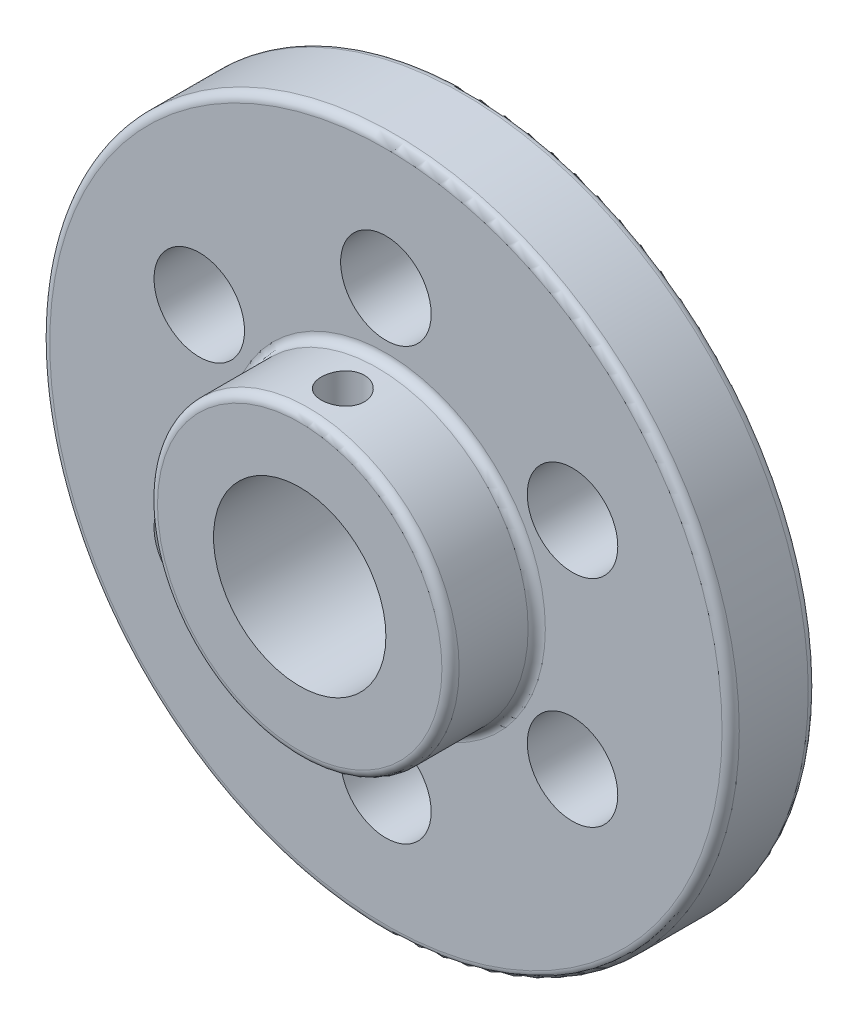
SolidWorks part; units mm, degrees
material "Gray Cast Iron"
ref_plane "Front Plane" through (0, 0, 0) normal (0, 0, 1) x (1, 0, 0)
ref_plane "Top Plane" through (0, 0, 0) normal (0, 1, 0) x (1, 0, 0)
ref_plane "Right Plane" through (0, 0, 0) normal (1, 0, 0) x (0, 0, -1)
sketch "Sketch1" plane through (0, 0, 0) normal (0, 0, 1) x (1, 0, 0)
  circle A0 centre (0, 0) radius 40
  circle A1 centre (0, 0) radius 10
  dimension "D1" = 80
  dimension "D2" = 20
extrude "Boss-Extrude1" add sketch "Sketch1" along normal blind 10
sketch "Sketch2" plane through (0, 0, 10) normal (0, 0, 1) x (1, 0, 0)
  circle A0 centre (0, 0) radius 25 construction
  circle A1 centre (0, 25) radius 5 construction
  dimension "D1" = 50
  dimension "D2" = 10
hole_wizard "M12x1.5 Tapped Hole1" positions "Sketch3" profile "Sketch4" tap size "M12x1.5" standard "ANSI Metric" end condition through all
sketch "Sketch3" plane through (0, 0, 10) normal (0, 0, 1) x (1, 0, 0)
  point P0 (0, 25)
sketch "Sketch4" plane through (0, 25, 10) normal (1, 0, 0) x (0, -1, 0)
  line L0 (0, 0) -> (0, 10)
  line L1 (0, 10) -> (5.25, 10)
  line L2 (5.25, 10) -> (5.25, 0)
  line L5 (5.25, 0) -> (0, 0)
  line L11 (0, -6.35) -> (0, 107.95) construction
  dimension "Thru Tap Drill Dia." = 10.5
  dimension "Thru Tap Drill Depth" = 10
cosmetic thread "Hole Thread1" parameters "D2"=12
pattern_circular "CirPattern1" count 6 over 360 about axis through (0, 0, 0) along (0, 0, 1) of "M12x1.5 Tapped Hole1"
cosmetic thread "Hole Thread2" parameters "D2"=12
cosmetic thread "Hole Thread3" parameters "D2"=12
cosmetic thread "Hole Thread4" parameters "D2"=12
cosmetic thread "Hole Thread5" parameters "D2"=12
cosmetic thread "Hole Thread6" parameters "D2"=12
sketch "Sketch5" plane through (0, 0, 10) normal (0, 0, 1) x (1, 0, 0)
  circle A0 centre (0, 0) radius 17.5
  circle A1 centre (0, 0) radius 10 construction
  circle A2 centre (0, 0) radius 10
  dimension "D1" = 35
extrude "Boss-Extrude2" add sketch "Sketch5" along normal blind 10
ref_plane "Plane1" through (0, 17.5, 0) normal (0, 1, 0) x (1, 0, 0)
sketch "Sketch6" plane through (0, 17.5, 0) normal (0, 1, 0) x (1, 0, 0)
  line L0 (-17.5, -20) -> (17.5, -20) construction
  line L1 (17.5, -20) -> (17.5, -10) construction
  line L2 (-17.5, -10) -> (17.5, -10) construction
  line L3 (-17.5, -10) -> (-17.5, -20) construction
  line L4 (-17.5, -20) -> (17.5, -20) construction
  line L5 (17.5, -20) -> (17.5, -10) construction
  line L6 (-17.5, -10) -> (17.5, -10) construction
  line L7 (-17.5, -10) -> (-17.5, -20) construction
  line L9 (-17.5, -10) -> (17.5, -10) construction
  line L10 (-17.5, -10) -> (-17.5, -20)
  line L11 (-17.5, -20) -> (17.5, -20)
  line L12 (17.5, -10) -> (17.5, -20)
  line L13 (-17.5, -10) -> (17.5, -20) construction
  line L14 (-17.5, -20) -> (17.5, -10) construction
  circle A0 centre (0, -15) radius 2.5
  point P5 (0, -15)
  dimension "D1" = 5
hole_wizard "M6x1.0 Tapped Hole1" positions "Sketch7" profile "Sketch8" tap size "M6x1.0" standard "ANSI Metric"
sketch "Sketch7" plane through (0, 17.5, 0) normal (0, 1, 0) x (1, 0, 0)
  point P0 (0, -15)
sketch "Sketch8" plane through (0, 17.5, 15) normal (1, 0, 0) x (0, 0, 1)
  line L0 (0, 0) -> (0, 7.5)
  line L1 (0, 7.5) -> (2.5, 7.5)
  line L2 (2.5, 7.5) -> (2.5, 0)
  line L5 (2.5, 0) -> (0, 0)
  line L11 (0, -6.35) -> (0, 107.95) construction
  dimension "Thru Tap Drill Dia." = 5
  dimension "Thru Tap Drill Depth" = 7.5
cosmetic thread "Hole Thread7" parameters "D2"=6
fillet "Fillet1" radius 1 4 edges at (17.5, 0, 20) (17.5, 0, 10) (40, 0, 0) (40, 0, 10)
